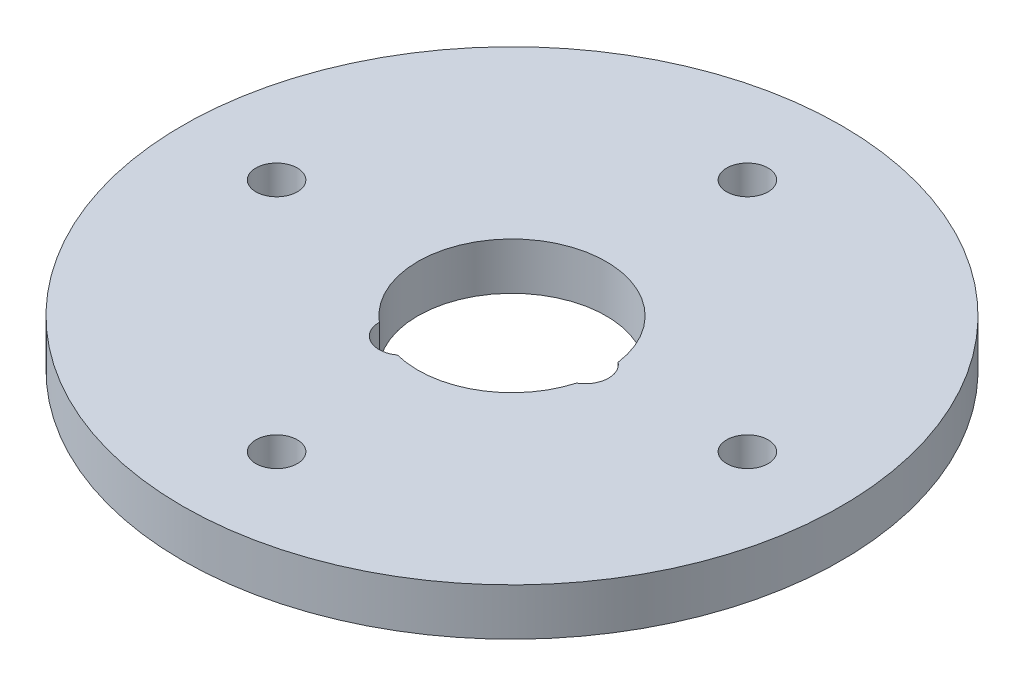
SolidWorks part; units mm, degrees
ref_plane "Front Plane" through (0, 0, 0) normal (0, 0, 1) x (1, 0, 0)
ref_plane "Top Plane" through (0, 0, 0) normal (0, 1, 0) x (1, 0, 0)
ref_plane "Right Plane" through (0, 0, 0) normal (1, 0, 0) x (0, 0, -1)
sketch "Sketch1" plane through (0, 0, 0) normal (0, 1, 0) x (1, 0, 0)
  circle A0 centre (0, 0) radius 35
  circle A1 centre (0, 25) radius 2.2
  circle A2 centre (25, 0) radius 2.2
  circle A3 centre (0, -25) radius 2.2
  circle A4 centre (-25, 0) radius 2.2
  circle A5 centre (0, 0) radius 10
  point P14 (0, 0)
  dimension "D1" = 70
  dimension "D2" = 4.4
  dimension "D5" = 20
  dimension "D3" = 25
  dimension "D4" = 4
extrude "Boss-Extrude1" add sketch "Sketch1" along normal blind 5
scale "Echelle2" bodies to scale 101 scale about centroid uniform scaling yes scale factor 2
sketch "Esquisse3" plane through (0, -2.5, 0) normal (0, -1, 0) x (1, 0, 0)
  circle A0 centre (16.7179, 1.1939) radius 5
  circle A1 centre (-7.8988, 15.3352) radius 5
extrude "Enlèv. mat.-Extru.1" cut sketch "Esquisse3" against normal blind 10
scale "Echelle3" scale about centroid uniform scaling yes scale factor 0.25
